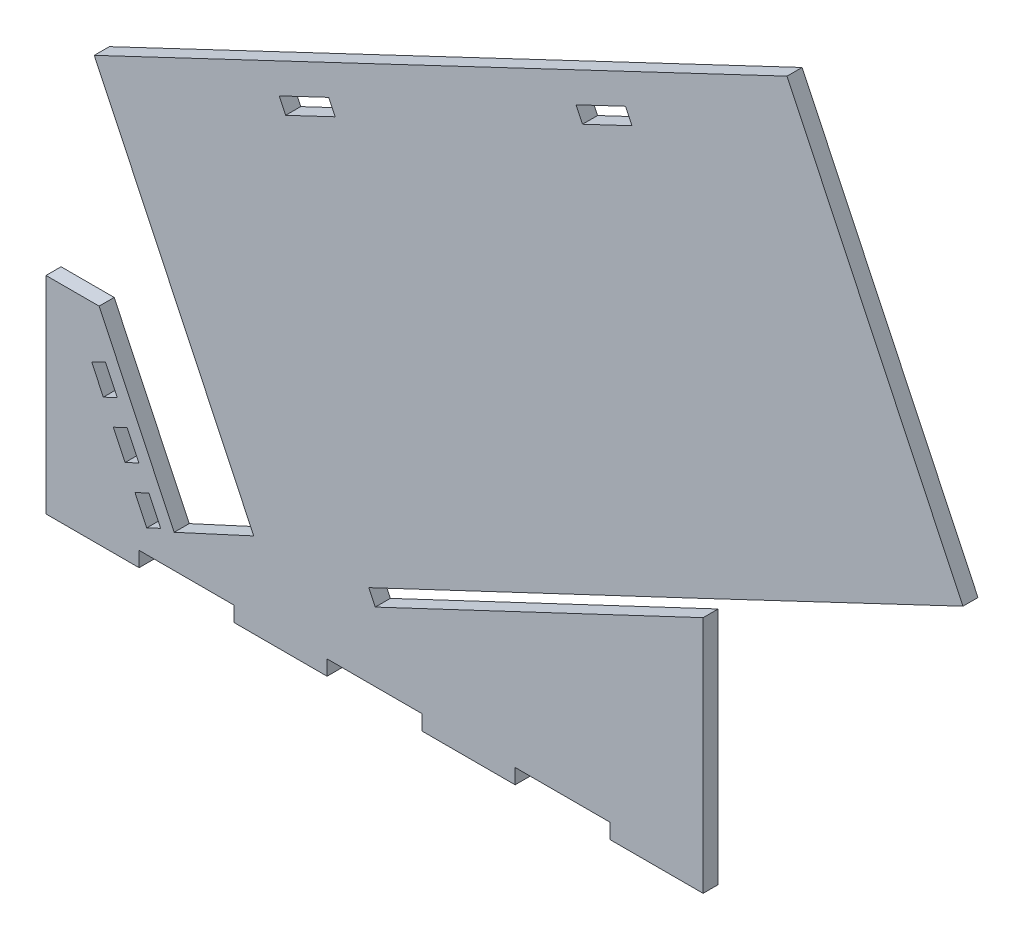
SolidWorks part; units mm, degrees
ref_plane "Alzado" through (0, 0, 0) normal (0, 0, 1) x (1, 0, 0)
ref_plane "Planta" through (0, 0, 0) normal (0, 1, 0) x (1, 0, 0)
ref_plane "Vista lateral" through (0, 0, 0) normal (1, 0, 0) x (0, 0, -1)
sketch "Croquis1" plane through (0, 0, 0) normal (0, 0, 1) x (1, 0, 0)
  line L1 (180, 0) -> (180, 93.2895)
  line L5 (-42.367, 153.888) -> (15.88, 30.9993)
  line L6 (-13.1889, 17.6155) -> (-40.6005, 75.4481)
  line L7 (-40.6005, 75.4481) -> (-60, 75.4481)
  line L8 (-60, 75.4481) -> (-60, 0)
  line L10 (-13.1889, 17.6155) -> (15.88, 30.9993)
  line L11 (-60, 0) -> (-26, 0)
  line L12 (-26, 0) -> (-26, 5.5)
  line L13 (-26, 5.5) -> (8.66, 5.5)
  line L14 (8.66, 5.5) -> (8.66, 0)
  line L15 (8.66, 0) -> (42.66, 0)
  line L16 (42.66, 0) -> (42.66, 5.5)
  line L17 (42.66, 5.5) -> (77.34, 5.5)
  line L18 (77.34, 5.5) -> (77.34, 0)
  line L19 (77.34, 0) -> (111.34, 0)
  line L20 (111.34, 0) -> (111.34, 5.5)
  line L21 (111.34, 5.5) -> (146, 5.5)
  line L22 (146, 5.5) -> (146, 0)
  line L23 (146, 0) -> (180, 0)
  line L24 (-42.367, 153.888) -> (210.6504, 273.8137)
  line L25 (210.6504, 273.8137) -> (274.8964, 138.2686)
  line L26 (274.8964, 138.2686) -> (180, 93.2895)
  dimension "D1" = 34
  dimension "D3" = 32
  dimension "D4" = 150
  dimension "D5" = 64
  dimension "D6" = 34
  dimension "D7" = 240
  dimension "D8" = 34
  dimension "D9" = 34
  dimension "D10" = 34.66
  dimension "D11" = 34.68
  dimension "D12" = 34.66
  dimension "D13" = 5.5
  dimension "D14" = 5.5
  dimension "D15" = 5.5
  dimension "D16" = 5.5
  dimension "D17" = 5.5
  dimension "D18" = 5.5
  dimension "D19" = 150
  dimension "D20" = 280
extrude "Saliente-Extruir1" add sketch "Croquis1" along normal blind 5.5
sketch "Croquis2" plane through (0, 0, 5.5) normal (0, 0, 1) x (1, 0, 0)
  line L4 (180, 93.2895) -> (57.9171, 35.6634)
  line L5 (57.9171, 35.6634) -> (60.2648, 30.6896)
  line L6 (60.2648, 30.6896) -> (180, 87.2075)
  line L7 (180, 0) -> (180, 93.2895) construction
  line L8 (180, 87.2075) -> (180, 93.2895)
  dimension "D1" = 135
  dimension "D2" = 5.5
extrude "Cortar-Extruir1" cut sketch "Croquis2" against normal blind 5.5
sketch "Croquis4" plane through (0, 0, 5.5) normal (0, 0, 1) x (1, 0, 0)
  line L5 (-43.3329, 56.4643) -> (-38.2726, 58.8628)
  line L6 (-38.2726, 58.8628) -> (-33.9895, 49.8265)
  line L7 (-33.9895, 49.8265) -> (-39.0499, 47.428)
  line L8 (-39.0499, 47.428) -> (-43.3329, 56.4643)
  line L9 (-35.4093, 39.7471) -> (-30.3489, 42.1456)
  line L10 (-30.3489, 42.1456) -> (-26.0659, 33.1093)
  line L11 (-26.0659, 33.1093) -> (-31.1262, 30.7108)
  line L12 (-31.1262, 30.7108) -> (-35.4093, 39.7471)
  line L13 (-27.4856, 23.0299) -> (-22.4253, 25.4284)
  line L14 (-22.4253, 25.4284) -> (-18.1422, 16.3921)
  line L15 (-18.1422, 16.3921) -> (-23.2026, 13.9935)
  line L16 (-27.4856, 23.0299) -> (-23.2026, 13.9935)
  line L17 (-13.1889, 17.6155) -> (-40.6005, 75.4481) construction
  dimension "D1" = 5
  dimension "D2" = 5
  dimension "D3" = 10
  dimension "D4" = 5
  dimension "D5" = 8.5
  dimension "D6" = 8.5
  dimension "D7" = 5.6
  dimension "D9" = 10
extrude "Cortar-Extruir4" cut sketch "Croquis4" against normal blind 5.5
sketch "Croquis5" plane through (0, 0, 5.5) normal (0, 0, 1) x (1, 0, 0)
  line L5 (25.1704, 174.8331) -> (27.5261, 169.8631)
  line L6 (27.5261, 169.8631) -> (45.5988, 178.4292)
  line L7 (45.5988, 178.4292) -> (43.2431, 183.3992)
  line L8 (43.2431, 183.3992) -> (25.1704, 174.8331)
  line L9 (133.6065, 226.2298) -> (151.6791, 234.7959)
  line L10 (151.6791, 234.7959) -> (154.0348, 229.8259)
  line L11 (154.0348, 229.8259) -> (135.9622, 221.2598)
  line L12 (135.9622, 221.2598) -> (133.6065, 226.2298)
  dimension "D1" = 5.5
  dimension "D2" = 20
  dimension "D7" = 100
extrude "Cortar-Extruir5" cut sketch "Croquis5" against normal blind 5.5
